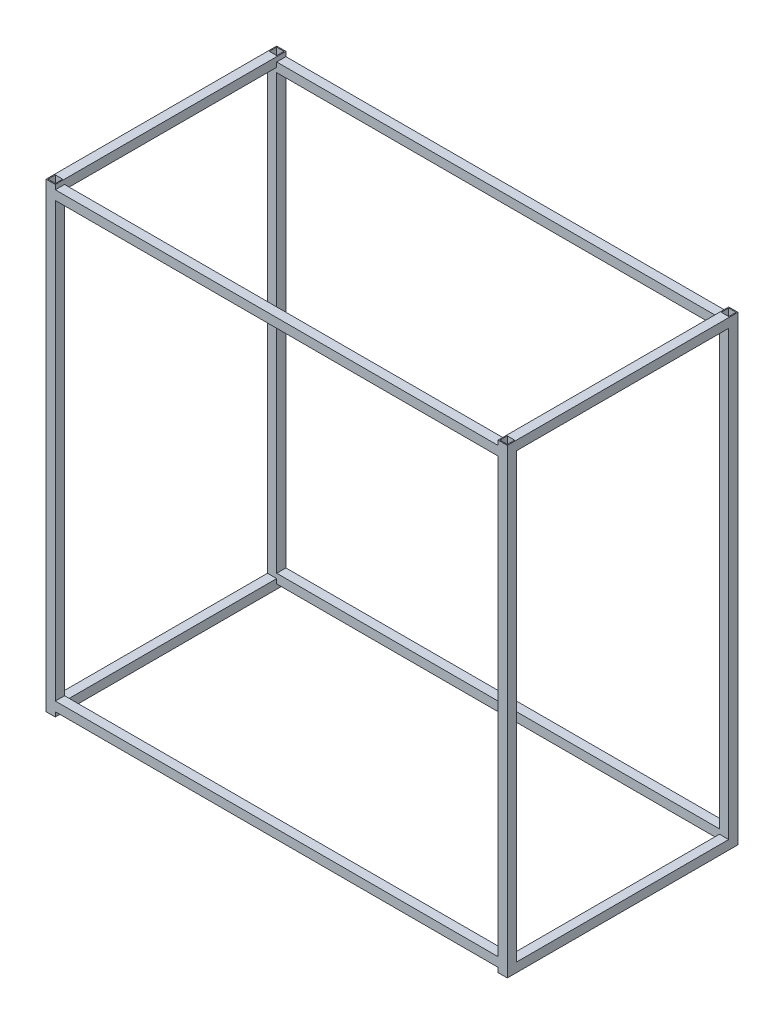
SolidWorks part; units mm, degrees
material "AISI 1035 Сталь (SS)"
ref_plane "Спереди" through (0, 0, 0) normal (0, 0, 1) x (1, 0, 0)
ref_plane "Сверху" through (0, 0, 0) normal (0, 1, 0) x (1, 0, 0)
ref_plane "Справа" through (0, 0, 0) normal (1, 0, 0) x (0, 0, -1)
sketch "Эскиз1" plane through (0, 0, 0) normal (0, 0, 1) x (1, 0, 0)
  line L0 (30, 1500) -> (30, 1485)
  line L1 (0, 0) -> (30, 0)
  line L2 (0, 0) -> (0, 1500)
  line L3 (0, 1500) -> (30, 1500)
  line L4 (1500, 0) -> (1500, 1500)
  line L5 (30, 1485) -> (1470, 1485)
  line L6 (1470, 1485) -> (1470, 1500)
  line L7 (1470, 0) -> (1470, 15)
  line L8 (1470, 15) -> (30, 15)
  line L9 (30, 15) -> (30, 0)
  line L10 (1470, 0) -> (1500, 0)
  line L11 (1470, 1500) -> (1500, 1500)
  line L13 (30, 1455) -> (1470, 1455)
  line L14 (30, 1455) -> (30, 45)
  line L15 (30, 45) -> (1470, 45)
  line L16 (1470, 1455) -> (1470, 45)
  dimension "D1" = 1500
  dimension "D2" = 1500
  dimension "D3" = 30
  dimension "D4" = 30
  dimension "D5" = 15
  dimension "D6" = 15
  dimension "D7" = 30
  dimension "D8" = 30
  dimension "D9" = 30
extrude "Бобышка-Вытянуть1" add sketch "Эскиз1" along normal blind 750
sketch "Эскиз2" plane through (1500, 0, 0) normal (1, 0, 0) x (0, 0, -1)
  line L0 (0, 1455) -> (0, 45) construction
  line L1 (-720, 1470) -> (-30, 1470)
  line L2 (-720, 1470) -> (-720, 30)
  line L3 (-720, 30) -> (-30, 30)
  line L4 (-30, 1470) -> (-30, 30)
  line L5 (-750, 0) -> (-750, 1500) construction
  line L6 (-750, 1500) -> (0, 1500) construction
  line L7 (-750, 0) -> (0, 0) construction
  dimension "D1" = 30
  dimension "D2" = 30
  dimension "D3" = 30
  dimension "D4" = 30
extrude "Вырез-Вытянуть1" cut sketch "Эскиз2" against normal through all
sketch "Эскиз3" plane through (0, 1485, 0) normal (0, 1, 0) x (1, 0, 0)
  line L0 (1470, -750) -> (1470, 0) construction
  line L1 (1470, -720) -> (30, -720)
  line L2 (1470, -720) -> (1470, -30)
  line L3 (1470, -30) -> (30, -30)
  line L4 (30, -720) -> (30, -30)
  line L5 (30, -750) -> (30, 0) construction
  line L6 (1470, -750) -> (30, -750) construction
  line L7 (30, 0) -> (1470, 0) construction
  dimension "D1" = 30
  dimension "D2" = 30
extrude "Вырез-Вытянуть2" cut sketch "Эскиз3" against normal through all
sketch "Эскиз4" plane through (0, 1500, 0) normal (0, 1, 0) x (1, 0, 0)
  line L0 (0, 0) -> (30, 0) construction
  line L1 (3, -3) -> (27, -3)
  line L2 (3, -3) -> (3, -27)
  line L3 (3, -27) -> (27, -27)
  line L4 (27, -3) -> (27, -27)
  line L5 (0, -750) -> (0, 0) construction
  line L6 (1470, -30) -> (30, -30) construction
  line L7 (1500, -750) -> (1500, 0) construction
  line L8 (1473, -723) -> (1497, -723)
  line L9 (1473, -723) -> (1473, -747)
  line L10 (1473, -747) -> (1497, -747)
  line L11 (1497, -723) -> (1497, -747)
  line L12 (1500, -750) -> (1470, -750) construction
  line L13 (30, -720) -> (1470, -720) construction
  line L14 (1470, -750) -> (1470, -720) construction
  line L16 (1473, -3) -> (1497, -3)
  line L17 (1473, -3) -> (1473, -27)
  line L18 (1473, -27) -> (1497, -27)
  line L19 (1497, -3) -> (1497, -27)
  line L20 (3, -723) -> (27, -723)
  line L21 (3, -723) -> (3, -747)
  line L22 (3, -747) -> (27, -747)
  line L23 (27, -723) -> (27, -747)
  dimension "D1" = 3
  dimension "D2" = 3
  dimension "D3" = 3
  dimension "D4" = 3
  dimension "D5" = 3
  dimension "D6" = 3
  dimension "D7" = 3
extrude "Вырез-Вытянуть3" cut sketch "Эскиз4" against normal through all
